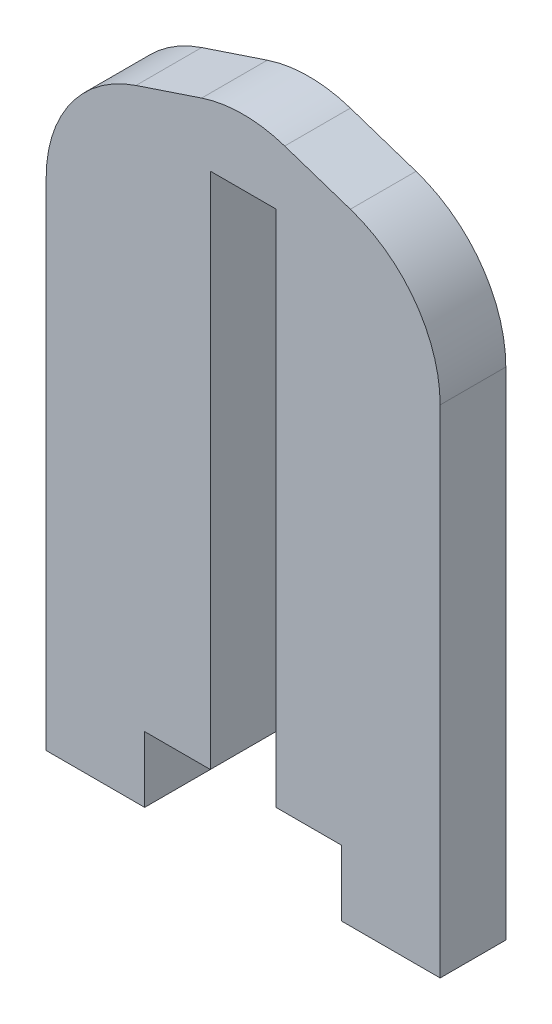
SolidWorks part; units mm, degrees
ref_plane "Front Plane" through (0, 0, 0) normal (0, 0, 1) x (1, 0, 0)
ref_plane "Top Plane" through (0, 0, 0) normal (0, 1, 0) x (1, 0, 0)
ref_plane "Right Plane" through (0, 0, 0) normal (1, 0, 0) x (0, 0, -1)
sketch "Sketch1" plane through (0, 0, 0) normal (0, 0, 1) x (1, 0, 0)
  line L0 (0, 25.4) -> (0, -25.4) construction
  line L1 (-9.525, -31.75) -> (9.525, -31.75)
  line L2 (-19.05, -31.75) -> (-19.05, 19.05)
  line L4 (19.05, -31.75) -> (19.05, 19.05)
  line L5 (9.525, -31.75) -> (9.525, -38.1)
  line L7 (-19.05, 0) -> (19.05, 0) construction
  line L8 (-19.05, -31.75) -> (-19.05, -38.1)
  line L9 (-19.05, -38.1) -> (-9.525, -38.1)
  line L10 (-9.525, -31.75) -> (-9.525, -38.1)
  line L11 (19.05, -38.1) -> (9.525, -38.1)
  line L12 (19.05, -31.75) -> (19.05, -38.1)
  line L13 (-19.05, 19.05) -> (19.05, 19.05) construction
  line L14 (-19.05, 19.05) -> (0, 25.4)
  line L15 (0, 25.4) -> (19.05, 19.05)
  point P0 (0, 0)
  dimension "D1" = 6.35
  dimension "D3" = 6.35
  dimension "D4" = 9.525
  dimension "D2" = 57.15
  dimension "D5" = 6.35
extrude "Boss-Extrude1" add sketch "Sketch1" along normal blind 6.35
fillet "Fillet1" radius 12.7 3 edges at (-19.05, 19.05, 3.175) (19.05, 19.05, 3.175) (0, 25.4, 3.175)
sketch "Sketch2" plane through (0, 0, 6.35) normal (0, 0, 1) x (1, 0, 0)
  line L0 (0, 24.713) -> (0, -31.75) construction
  line L1 (-9.525, -31.75) -> (9.525, -31.75) construction
  line L2 (-19.05, -0.7037) -> (19.05, -0.7037) construction
  line L3 (-19.05, 9.8964) -> (-19.05, -38.1) construction
  line L4 (19.05, -38.1) -> (19.05, 9.8964) construction
  line L6 (-3.175, 18.363) -> (3.175, 18.363)
  line L7 (-3.175, 18.363) -> (-3.175, -31.75)
  line L8 (-3.175, -31.75) -> (3.175, -31.75)
  line L9 (3.175, 18.363) -> (3.175, -31.75)
  arc A0 (4.0161, 24.0613) -> (-4.0161, 24.0613) centre (0, 12.013) ccw construction
  point P13 (0, -11.1355)
  dimension "D1" = 6.35
  dimension "D2" = 6.35
  dimension "D3" = 3.175
extrude "Cut-Extrude1" cut sketch "Sketch2" against normal through all both and the other way through all
equation "\"Wheel Thickness\"= 1in"
equation "\"Wheel Diameter\"= 3in"
equation "\"Motor Rear Diameter\" = 36.2mm"
equation "\"Motor Front Diameter\" = 12mm"
equation "\"Material Thickness\" = .25in"
equation "\"Wheel Cutout Diameter\"= 2cm"
equation "\"Motor Mount Tab Thickness\" = 100mm"
equation "\"Motor Mount Tab Height\" = 40mm"
equation "\"Motor Shaft Diameter\" = 3mm"
equation "\"Wheel Radius Clearance\" = 5mm"
equation "\"Wheel Cutout Width\" = 1.5in"
equation "\"Base Diameter\" = 10in"
equation "\"Wheel Mount Distance\" = 5mm"
equation "\"Motor Mount Distance\" = 50mm"
equation "\"Motor Cutout Length\" = 6in"
equation "\"Motor Cutout Height\" = 2in "
equation "\"Rod Diameter\" = 3/8in"
equation "\"Rod Length\" = 1.5in"
equation "\"Barrel Front Length\" = 1.8in"
equation "\"Barrerl Rear Length\" = 5in "
equation "\"Barrel Fillet Radius\" = 1in "
equation "\"Barrel Angle\" = 20deg"
equation "\"Barrel Diameter\" = 50mm"
equation "\"Barrel Shell Width\" = 2mm"
equation "\"Second Level Diameter\" = 10in"
equation "\"Ball Diameter\" = 40mm"
equation "\"Third Level Length\" = 9in"
equation "\"Third Level Height\" = 9in"
equation "\"Barrel Tab Clearance\" = 5mm"
equation "\"Barrel Tab Distance Away\" = 2mm"
equation "\"Hole Distance Apart\" = 2.8in"
equation "\"Barrel Tab Distance\"= 1.5in "
equation "\"Third Level Rod Distance\" = .5in"
equation " \"Second Rod Diameter\" = 3/8in"
equation "\"Second Rod Length\" = 3.88in"
equation "\"Bumper Wheel Clearance\" = 1.2in"
equation "\"Servo Tab Height\" = 4in"
equation "\"Servo Tab Width\" = 2in"
equation "\"Servo Tab Hole Horizontal Distance\" = 1in"
equation "\"Servo Tab Hole Vertical Distance\" = 1.5in "
equation "\"Servo Hole Vertical Distance\" = 3in"
equation "\"Servo Hole Diameter\" = 1/4in"
equation "\"Servo Hole Shaft Length\" = 1.45in"
equation "\"Third Rod Length\" = 3.83in"
equation "\"Third Rod Diameter\" = 3/8in"
equation "\"Third Rod Radius Distance\" = 1.5in"
equation "\"Third Rod Angle Distance\" = 20deg"
equation "\"Fourth Level Diameter\" = 3.5in"
equation "\"Skid Length\" = 2in"
equation "\"Skid Width\" = 1.5in"
equation "\"Skid Clearance\" = 3mm"
equation "\"Skid Cut Distance\" = .25in"
equation "\"D1@Boss-Extrude1\"=\"Material Thickness\""
equation "\"Skid Fillet Radius\" = .5in"
equation "\"D3@Sketch1\"=\"Material Thickness\""
equation "\"D4@Sketch1\"=\"Skid Width\"/4"
equation "\"D1@Fillet1\"=\"Skid Fillet Radius\""
equation "\"D1@Sketch2\"=\"Skid Cut Distance\""
equation "\"D1@Sketch1\"=\"Material Thickness\""
equation "\"D2@Sketch1\"=\"Skid Length\"+(\"Skid Length\"/8)"
equation "\"D2@Sketch2\"=\"Material Thickness\""
equation "\"D3@Sketch2\"=\"Material Thickness\"/2"
equation "\"D5@Sketch1\"=\"Skid Length\"/8"
